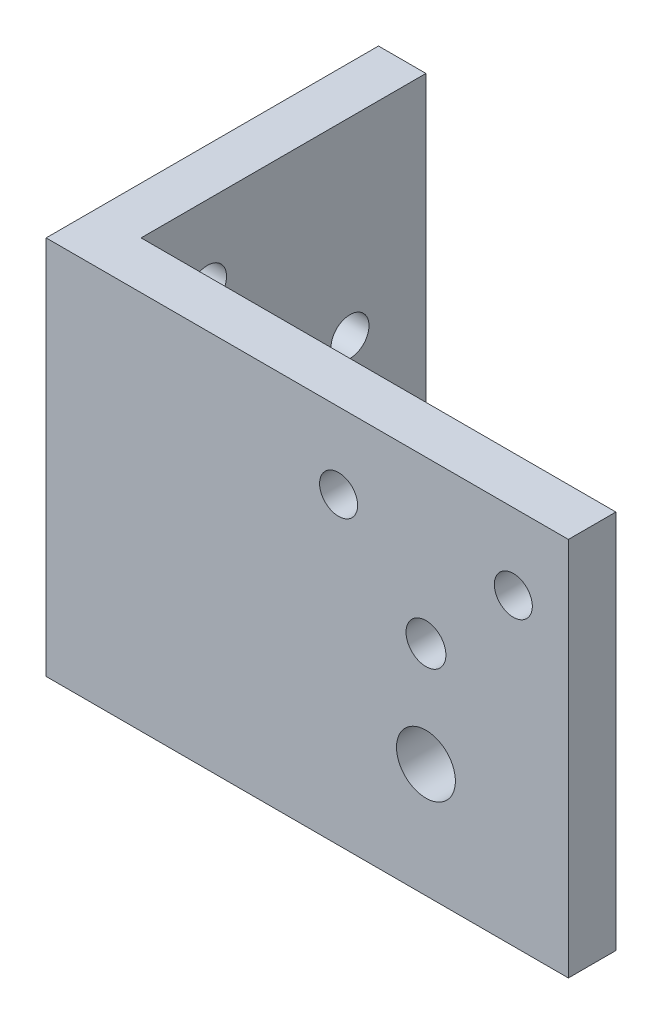
SolidWorks part; units mm, degrees
ref_plane "Front Plane" through (0, 0, 0) normal (0, 0, 1) x (1, 0, 0)
ref_plane "Top Plane" through (0, 0, 0) normal (0, 1, 0) x (1, 0, 0)
ref_plane "Right Plane" through (0, 0, 0) normal (1, 0, 0) x (0, 0, -1)
sketch "Sketch1" plane through (0, 0, 0) normal (0, 1, 0) x (1, 0, 0)
  line L0 (0, 0) -> (55, 0)
  line L1 (55, 0) -> (55, 5)
  line L2 (55, 5) -> (5, 5)
  line L3 (5, 5) -> (5, 35)
  line L4 (5, 35) -> (0, 35)
  line L5 (0, 35) -> (0, 0)
  dimension "D1" = 55
  dimension "D2" = 5
  dimension "D3" = 35
  dimension "D4" = 5
extrude "Boss-Extrude2" add sketch "Sketch1" along normal blind 40 contours L5 L0 L1 L2 L3 L4
sketch "Sketch3" plane through (0, 0, -5) normal (0, 0, -1) x (-1, 0, 0)
  line L0 (-55, 40) -> (-55, 0) construction
  circle A0 centre (-40, 12) radius 3.1
  circle A1 centre (-40, 23) radius 2.1
  circle A2 centre (-49.2, 32) radius 2
  circle A3 centre (-30.8, 32) radius 2
  dimension "D4" = 6.2
  dimension "D5" = 4.2
  dimension "D8" = 4
  dimension "D9" = 4
  dimension "D1" = 15
  dimension "D2" = 15
  dimension "D3" = 11
  dimension "D6" = 5.8
  dimension "D7" = 18.4
extrude "Cut-Extrude1" cut sketch "Sketch3" against normal through all
sketch "Sketch4" plane through (5, 0, 0) normal (1, 0, 0) x (0, 0, -1)
  line L0 (5, 40) -> (12, 40)
  line L1 (5, 40) -> (35, 40) construction
  circle A2 centre (27, 20) radius 2
  circle A3 centre (12, 32) radius 2
  circle A4 centre (12, 8) radius 2
  dimension "D2" = 4
extrude "Cut-Extrude3" cut sketch "Sketch4" against normal through all contours A3 | A2 | A4
